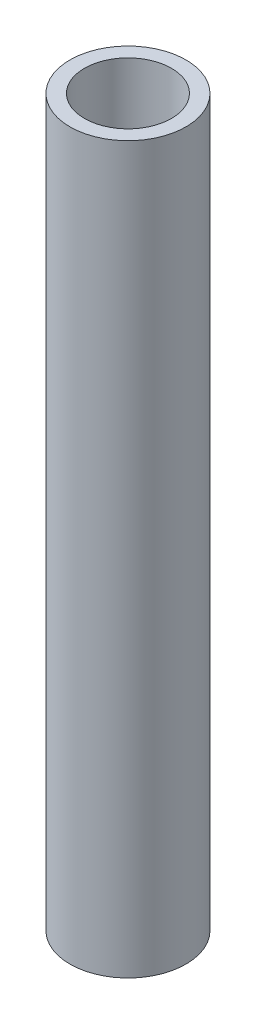
SolidWorks part; units mm, degrees
ref_plane "Front Plane" through (0, 0, 0) normal (0, 0, 1) x (1, 0, 0)
ref_plane "Top Plane" through (0, 0, 0) normal (0, 1, 0) x (1, 0, 0)
ref_plane "Right Plane" through (0, 0, 0) normal (1, 0, 0) x (0, 0, -1)
sketch "Sketch1" plane through (0, 0, 0) normal (0, 0, 1) x (1, 0, 0)
  line L0 (0, 0) -> (0, 50)
  point P6 (0, 50)
  dimension "D1" = 50
sketch "Sketch2" plane through (0, 0, 0) normal (0, 1, 0) x (1, 0, 0)
  circle A0 centre (0, 0) radius 4
  circle A1 centre (0, 0) radius 3
  dimension "D1" = 6
  dimension "D2" = 8
sweep "Sweep1" add profiles "Sketch2" path "Sketch1"
